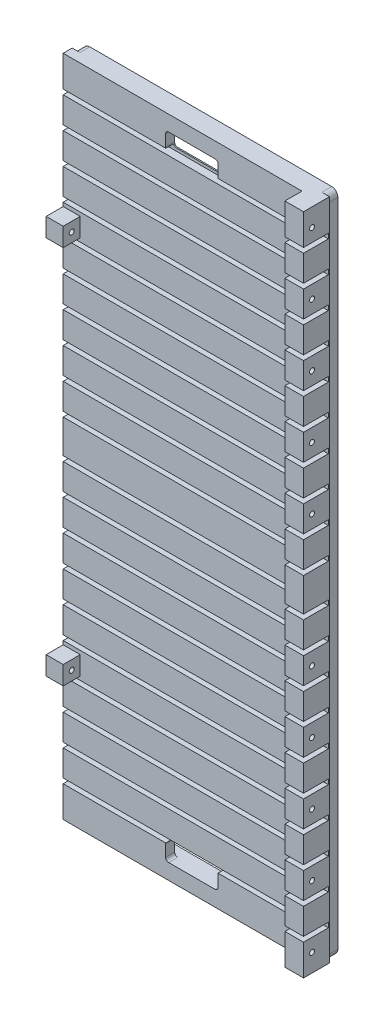
SolidWorks part; units mm, degrees
ref_plane "Front Plane" through (0, 0, 0) normal (0, 0, 1) x (1, 0, 0)
ref_plane "Top Plane" through (0, 0, 0) normal (0, 1, 0) x (1, 0, 0)
ref_plane "Right Plane" through (0, 0, 0) normal (1, 0, 0) x (0, 0, -1)
sketch "Sketch1" plane through (0, 0, 0) normal (0, 0, 1) x (1, 0, 0)
  line L1 (-41.5, -107) -> (41.5, -107)
  line L2 (-41.5, -107) -> (-41.5, 107)
  line L3 (-41.5, 107) -> (41.5, 107)
  line L4 (41.5, -107) -> (41.5, 107)
  line L5 (-41.5, -107) -> (41.5, 107) construction
  line L6 (-41.5, 107) -> (41.5, -107) construction
  point P0 (0, 0)
  dimension "D1" = 83
  dimension "D2" = 214
extrude "Boss-Extrude1" add sketch "Sketch1" along normal blind 8.4
sketch "Sketch2" plane through (0, 107, 0) normal (0, 1, 0) x (1, 0, 0)
  line L0 (41.5, -8.4) -> (41.5, 0) construction
  line L1 (-41.5, -8.4) -> (35.5, -8.4)
  line L2 (-41.5, -8.4) -> (-41.5, -2.9)
  line L3 (-41.5, -2.9) -> (35.5, -2.9)
  line L4 (35.5, -8.4) -> (35.5, -2.9)
  dimension "D1" = 5.5
  dimension "D2" = 6
extrude "Cut-Extrude1" cut sketch "Sketch2" against normal through all
sketch "Sketch3" plane through (41.5, 0, 0) normal (1, 0, 0) x (0, 0, -1)
  line L0 (-8.4, -107) -> (-8.4, 107) construction
  line L1 (-8.4, 97) -> (-0.4, 97)
  line L2 (-8.4, 97) -> (-8.4, 95.4)
  line L3 (-8.4, 95.4) -> (-0.4, 95.4)
  line L4 (-0.4, 97) -> (-0.4, 95.4)
  line L5 (-8.4, 107) -> (0, 107) construction
  dimension "D1" = 1.6
  dimension "D2" = 8
  dimension "D3" = 10
extrude "Cut-Extrude2" cut sketch "Sketch3" against normal through all
pattern_linear "LPattern1" count 10 spacing 10 along (0, -1, 0) of "Cut-Extrude2"
mirror "Mirror1" about plane through (0, 0, 0) normal (0, 1, 0) of "LPattern1", "Cut-Extrude2"
sketch "Sketch4" plane through (0, 0, 0) normal (0, 0, -1) x (-1, 0, 0)
  line L0 (-41.5, 107) -> (41.5, 107) construction
  line L1 (-39, 107) -> (39, 107)
  line L2 (-41, 105) -> (-41, -105)
  line L3 (-39, -107) -> (39, -107)
  line L4 (41, 105) -> (41, -105)
  line L5 (-33.5, -102) -> (33.5, -102)
  line L6 (-35.5, -100) -> (-35.5, 100)
  line L7 (-33.5, 102) -> (33.5, 102)
  line L8 (35.5, -100) -> (35.5, 100)
  line L9 (-35.5, -102) -> (35.5, 102) construction
  line L10 (-35.5, 102) -> (35.5, -102) construction
  line L11 (41.5, -107) -> (-41.5, -107) construction
  arc A0 (-41, -105) -> (-39, -107) centre (-39, -105) ccw
  arc A1 (39, -107) -> (41, -105) centre (39, -105) ccw
  arc A2 (39, 107) -> (41, 105) centre (39, 105) cw
  arc A3 (-39, 107) -> (-41, 105) centre (-39, 105) ccw
  arc A4 (33.5, -102) -> (35.5, -100) centre (33.5, -100) ccw
  arc A5 (-33.5, -102) -> (-35.5, -100) centre (-33.5, -100) cw
  arc A6 (-35.5, 100) -> (-33.5, 102) centre (-33.5, 100) cw
  arc A7 (33.5, 102) -> (35.5, 100) centre (33.5, 100) cw
  point P10 (41.5, -107)
  point P15 (-41.5, 107)
  point P16 (0, 0)
  dimension "D1" = 2
  dimension "D4" = 2
  dimension "D2" = 5
  dimension "D3" = 5.5
  dimension "D5" = 41
  dimension "D6" = 41
extrude "Boss-Extrude2" add sketch "Sketch4" along normal blind 3.18
sketch "Sketch5" plane through (0, 0, 2.9) normal (0, 0, 1) x (1, 0, 0)
  line L0 (-41.5, 57) -> (-41.5, 65.4) construction
  line L1 (-36, 58.2) -> (-41.5, 58.2)
  line L2 (-36, 58.2) -> (-36, 64.2)
  line L3 (-36, 64.2) -> (-41.5, 64.2)
  line L4 (-41.5, 58.2) -> (-41.5, 64.2)
  line L5 (-36, 58.2) -> (-41.5, 64.2) construction
  line L6 (-36, 64.2) -> (-41.5, 58.2) construction
  line L8 (35.5, 65.4) -> (-41.5, 65.4) construction
  point P0 (-38.75, 61.2)
  dimension "D1" = 6
  dimension "D2" = 5.5
  dimension "D3" = 4.2
extrude "Boss-Extrude3" add sketch "Sketch5" along normal blind 5.5
mirror "Mirror2" about plane through (0, 0, 0) normal (0, 1, 0) of "Boss-Extrude3"
sketch "Sketch6" plane through (0, 0, 0) normal (0, 0, -1) x (-1, 0, 0)
  line L0 (33.5, 102) -> (-33.5, 102) construction
  line L1 (-7.475, 96.3) -> (7.475, 96.3)
  line L2 (-8.475, 97.3) -> (-8.475, 101)
  line L3 (-7.475, 102) -> (7.475, 102)
  line L4 (8.475, 97.3) -> (8.475, 101)
  line L5 (-8.475, 96.3) -> (8.475, 102) construction
  line L6 (-8.475, 102) -> (8.475, 96.3) construction
  arc A0 (-8.475, 101) -> (-7.475, 102) centre (-7.475, 101) cw
  arc A1 (7.475, 102) -> (8.475, 101) centre (7.475, 101) cw
  arc A2 (7.475, 96.3) -> (8.475, 97.3) centre (7.475, 97.3) ccw
  arc A3 (-7.475, 96.3) -> (-8.475, 97.3) centre (-7.475, 97.3) cw
  point P0 (0, 99.15)
  dimension "D3" = 1
  dimension "D1" = 5.7
  dimension "D2" = 16.95
extrude "Cut-Extrude3" cut sketch "Sketch6" against normal through all
mirror "Mirror3" about plane through (0, 0, 0) normal (0, 1, 0) of "Cut-Extrude3"
hole_wizard "M2x0.4 Tapped Hole1" positions "Sketch8" profile "Sketch7" tap size "M2x0.4" standard "ANSI Metric" end condition through all
sketch "Sketch8" plane through (41.5, 0, 0) normal (1, 0, 0) x (0, 0, -1)
  line L0 (-8.4, 97) -> (-8.4, 107) construction
  line L1 (-8.4, 107) -> (0, 107) construction
  line L2 (0, 0) -> (-25.7972, 0) construction
  line L3 (0, -107) -> (0, 107) construction
  point P0 (-5.65, 101.2)
  point P16 (-5.65, 81.2)
  point P17 (-5.65, 61.2)
  point P18 (-5.65, 41.2)
  point P19 (-5.65, 21.2)
  point P34 (-5.65, -101.2)
  point P35 (-5.65, -81.2)
  point P36 (-5.65, -61.2)
  point P37 (-5.65, -41.2)
  point P38 (-5.65, -21.2)
  dimension "D1" = 2.75
  dimension "D2" = 5.8
  dimension "D3" = 5
sketch "Sketch7" plane through (41.5, 101.2, 5.65) normal (0, 1, 0) x (0, 0, -1)
  line L0 (0, 0) -> (0, 83)
  line L1 (0, 83) -> (0.8, 83)
  line L2 (0.8, 83) -> (0.8, 0)
  line L5 (0.8, 0) -> (0, 0)
  line L11 (0, -6.35) -> (0, 107.95) construction
  dimension "Thread Major Dia." = 1.6
  dimension "Thru Tap Drill Depth" = 83
hole_wizard "M2x0.4 Tapped Hole2" positions "Sketch10" profile "Sketch11" tap size "M2x0.4" standard "ANSI Metric"
sketch "Sketch10" plane through (0, 0, -3.18) normal (0, 0, -1) x (-1, 0, 0)
  line L0 (39, 107) -> (-39, 107) construction
  line L1 (-41, 105) -> (-41, -105) construction
  line L3 (-35.5, 0) -> (35.5, 0) construction
  line L4 (-35.5, 100) -> (-35.5, -100) construction
  line L5 (35.5, -100) -> (35.5, 100) construction
  point P0 (-37.5, 101.2)
  point P15 (37.5, 101.2)
  point P16 (37.5, 81.2)
  point P17 (37.5, 61.2)
  point P18 (37.5, 41.2)
  point P19 (37.5, 21.2)
  point P20 (-37.5, 81.2)
  point P21 (-37.5, 61.2)
  point P22 (-37.5, 41.2)
  point P23 (-37.5, 21.2)
  point P32 (37.5, -101.2)
  point P33 (-37.5, -21.2)
  point P34 (-37.5, -41.2)
  point P35 (-37.5, -61.2)
  point P36 (-37.5, -81.2)
  point P37 (37.5, -21.2)
  point P38 (37.5, -41.2)
  point P39 (37.5, -61.2)
  point P40 (37.5, -81.2)
  point P41 (-37.5, -101.2)
  dimension "D1" = 5.8
  dimension "D2" = 3.5
  dimension "D5" = 2
  dimension "D3" = 5
sketch "Sketch11" plane through (37.5, 101.2, -3.18) normal (1, 0, 0) x (0, 1, 0)
  line L0 (0, 0) -> (0, 4.4807)
  line L1 (0, 4.4807) -> (0.8, 4)
  line L2 (0.8, 4) -> (0.8, 0)
  line L5 (0.8, 0) -> (0, 0)
  line L10 (0, 4.4807) -> (-0.8, 4) construction
  line L11 (0, -6.35) -> (0, 107.95) construction
  dimension "Tap Drill Dia." = 1.6
  dimension "Tap Drill Depth" = 4
  dimension "Drill Angle" = 118
sketch "Sketch12" plane through (0, 0, 2.9) normal (0, 0, 1) x (1, 0, 0)
  line L1 (28, 71.95) -> (34.5, 71.95)
  line L2 (27, 72.95) -> (27, 79.45)
  line L3 (28, 80.45) -> (34.5, 80.45)
  line L4 (35.5, 72.95) -> (35.5, 79.45)
  line L5 (-35.714, 77) -> (-35.714, 75.4) construction
  line L6 (-41.5, 77) -> (35.5, 77) construction
  line L7 (35.5, 75.4) -> (-41.5, 75.4) construction
  line L8 (41.5, 67) -> (41.5, 75.4) construction
  arc A0 (35.5, 72.95) -> (34.5, 71.95) centre (34.5, 72.95) cw
  arc A1 (34.5, 80.45) -> (35.5, 79.45) centre (34.5, 79.45) cw
  arc A2 (27, 79.45) -> (28, 80.45) centre (28, 79.45) cw
  arc A3 (27, 72.95) -> (28, 71.95) centre (28, 72.95) ccw
  point P6 (27, 76.2)
  point P19 (-35.714, 76.2)
  dimension "D1" = 1
  dimension "D2" = 8.5
  dimension "D3" = 8.5
  dimension "D4" = 6
extrude "wonky_+Y_RBF_hole" [suppressed] cut sketch "Sketch12" against normal blind 10
